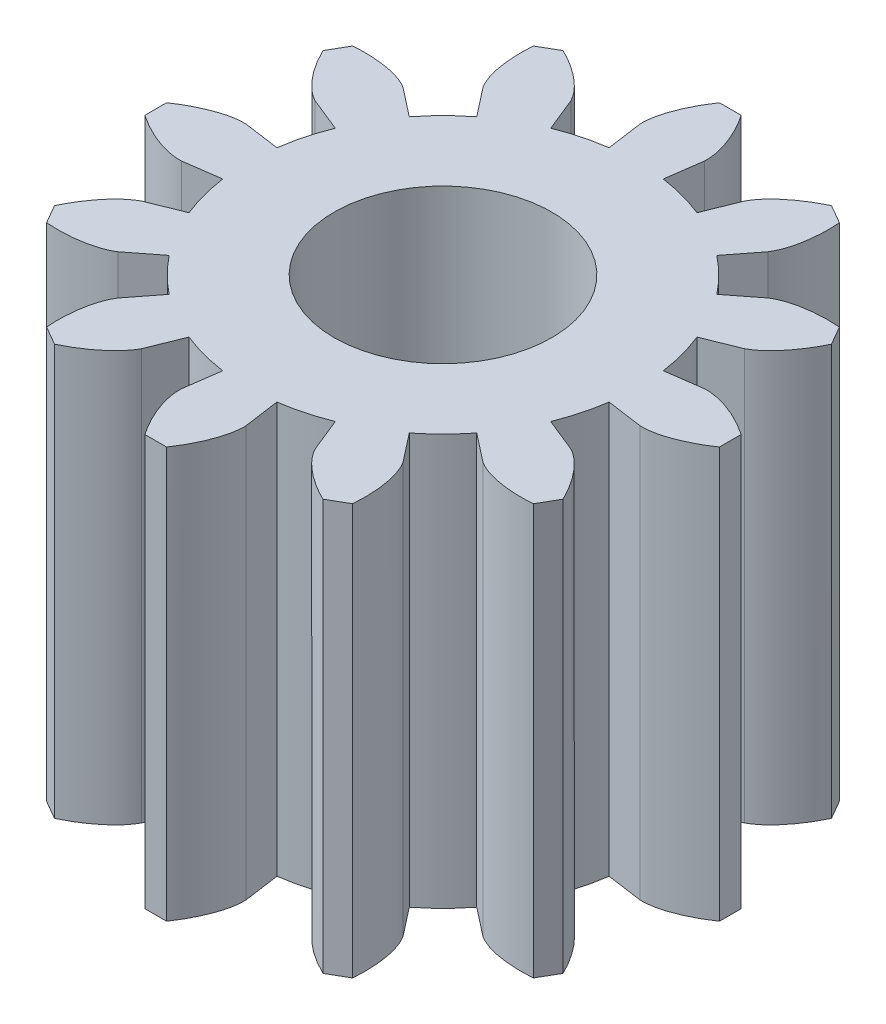
SolidWorks part; units mm, degrees
ref_plane "Front Plane" through (0, 0, 0) normal (0, 0, 1) x (1, 0, 0)
ref_plane "Top Plane" through (0, 0, 0) normal (0, 1, 0) x (1, 0, 0)
ref_plane "Right Plane" through (0, 0, 0) normal (1, 0, 0) x (0, 0, -1)
ref_plane "Plane1" through (0, -5, 0) normal (0, -1, 0) x (1, 0, 0)
sketch "Sketch1" plane through (0, -5, 0) normal (0, -1, 0) x (1, 0, 0)
  line L0 (3.7441, -2.923) -> (4.4442, -3.4696)
  line L1 (5.9256, -3.7266) -> (6.1901, -3.2684)
  line L2 (5.2268, -2.114) -> (4.4035, -1.781)
  line L3 (4.704, -0.6593) -> (5.5836, -0.7826)
  line L4 (6.995, -0.2646) -> (6.995, 0.2646)
  line L5 (5.5836, 0.7826) -> (4.704, 0.6593)
  line L6 (4.4035, 1.781) -> (5.2268, 2.114)
  line L7 (6.1901, 3.2684) -> (5.9256, 3.7266)
  line L8 (4.4442, 3.4696) -> (3.7441, 2.923)
  line L9 (2.923, 3.7441) -> (3.4696, 4.4442)
  line L10 (3.7266, 5.9256) -> (3.2684, 6.1901)
  line L11 (2.114, 5.2268) -> (1.781, 4.4035)
  line L12 (0.6593, 4.704) -> (0.7826, 5.5836)
  line L13 (0.2646, 6.995) -> (-0.2646, 6.995)
  line L14 (-0.7826, 5.5836) -> (-0.6593, 4.704)
  line L15 (-1.781, 4.4035) -> (-2.114, 5.2268)
  line L16 (-3.2684, 6.1901) -> (-3.7266, 5.9256)
  line L17 (-3.4696, 4.4442) -> (-2.923, 3.7441)
  line L18 (-3.7441, 2.923) -> (-4.4442, 3.4696)
  line L19 (-5.9256, 3.7266) -> (-6.1901, 3.2684)
  line L20 (-5.2268, 2.114) -> (-4.4035, 1.781)
  line L21 (-4.704, 0.6593) -> (-5.5836, 0.7826)
  line L22 (-6.995, 0.2646) -> (-6.995, -0.2646)
  line L23 (-5.5836, -0.7826) -> (-4.704, -0.6593)
  line L24 (-4.4035, -1.781) -> (-5.2268, -2.114)
  line L25 (-6.1901, -3.2684) -> (-5.9256, -3.7266)
  line L26 (-4.4442, -3.4696) -> (-3.7441, -2.923)
  line L27 (-2.923, -3.7441) -> (-3.4696, -4.4442)
  line L28 (-3.7266, -5.9256) -> (-3.2684, -6.1901)
  line L29 (-2.114, -5.2268) -> (-1.781, -4.4035)
  line L30 (-0.6593, -4.704) -> (-0.7826, -5.5836)
  line L31 (-0.2646, -6.995) -> (0.2646, -6.995)
  line L32 (0.7826, -5.5836) -> (0.6593, -4.704)
  line L33 (1.781, -4.4035) -> (2.114, -5.2268)
  line L34 (3.2684, -6.1901) -> (3.7266, -5.9256)
  line L35 (3.4696, -4.4442) -> (2.923, -3.7441)
  arc A0 (2.923, -3.7441) -> (3.7441, -2.923) centre (0, 0) ccw
  arc A1 (4.4035, -1.781) -> (4.704, -0.6593) centre (0, 0) ccw
  arc A2 (4.704, 0.6593) -> (4.4035, 1.781) centre (0, 0) ccw
  arc A3 (3.7441, 2.923) -> (2.923, 3.7441) centre (0, 0) ccw
  arc A4 (1.781, 4.4035) -> (0.6593, 4.704) centre (0, 0) ccw
  arc A5 (-0.6593, 4.704) -> (-1.781, 4.4035) centre (0, 0) ccw
  arc A6 (-2.923, 3.7441) -> (-3.7441, 2.923) centre (0, 0) ccw
  arc A7 (-4.4035, 1.781) -> (-4.704, 0.6593) centre (0, 0) ccw
  arc A8 (-4.704, -0.6593) -> (-4.4035, -1.781) centre (0, 0) ccw
  arc A9 (-3.7441, -2.923) -> (-2.923, -3.7441) centre (0, 0) ccw
  arc A10 (-1.781, -4.4035) -> (-0.6593, -4.704) centre (0, 0) ccw
  arc A11 (0.6593, -4.704) -> (1.781, -4.4035) centre (0, 0) ccw
  ellipse E0 centre (5.8654, -2.9875) end of major axis (7.546, -2.8631) minor radius 0.7415 (4.4442, -3.4696) -> (5.9256, -3.7266) ccw
  ellipse E1 centre (5.5279, -3.5513) end of major axis (6.2585, -5.0325) minor radius 0.7192 (6.1901, -3.2684) -> (5.2268, -2.114) ccw
  ellipse E2 centre (6.5733, 0.3454) end of major axis (7.9666, 1.2935) minor radius 0.7415 (5.5836, -0.7826) -> (6.995, -0.2646) ccw
  ellipse E3 centre (6.563, -0.3115) end of major axis (7.9362, -1.229) minor radius 0.7192 (6.995, 0.2646) -> (5.5836, 0.7826) ccw
  ellipse E4 centre (5.5199, 3.5858) end of major axis (4.7874, 2.068) minor radius 0.7415 (5.2268, 2.114) -> (6.1901, 3.2684) ccw
  ellipse E5 centre (5.8394, 3.0117) end of major axis (7.4875, 2.9038) minor radius 0.7192 (5.9256, 3.7266) -> (4.4442, 3.4696) ccw
  ellipse E6 centre (2.9875, 5.8654) end of major axis (3.112, 4.1847) minor radius 0.7415 (3.4696, 4.4442) -> (3.7266, 5.9256) ccw
  ellipse E7 centre (3.5513, 5.5279) end of major axis (5.0325, 6.2585) minor radius 0.7192 (3.2684, 6.1901) -> (2.114, 5.2268) ccw
  ellipse E8 centre (-0.3454, 6.5733) end of major axis (0.6027, 5.18) minor radius 0.7415 (0.7826, 5.5836) -> (0.2646, 6.995) ccw
  ellipse E9 centre (0.3115, 6.563) end of major axis (-0.606, 5.1897) minor radius 0.7192 (-0.2646, 6.995) -> (-0.7826, 5.5836) ccw
  ellipse E10 centre (-3.5858, 5.5199) end of major axis (-2.068, 4.7874) minor radius 0.7415 (-2.114, 5.2268) -> (-3.2684, 6.1901) ccw
  ellipse E11 centre (-3.0117, 5.8394) end of major axis (-3.1197, 4.1914) minor radius 0.7192 (-3.7266, 5.9256) -> (-3.4696, 4.4442) ccw
  ellipse E12 centre (-5.8654, 2.9875) end of major axis (-4.1847, 3.112) minor radius 0.7415 (-4.4442, 3.4696) -> (-5.9256, 3.7266) ccw
  ellipse E13 centre (-5.5279, 3.5513) end of major axis (-4.7974, 2.07) minor radius 0.7192 (-6.1901, 3.2684) -> (-5.2268, 2.114) ccw
  ellipse E14 centre (-6.5733, -0.3454) end of major axis (-5.18, 0.6027) minor radius 0.7415 (-5.5836, 0.7826) -> (-6.995, 0.2646) ccw
  ellipse E15 centre (-6.563, 0.3115) end of major axis (-5.1897, -0.606) minor radius 0.7192 (-6.995, -0.2646) -> (-5.5836, -0.7826) ccw
  ellipse E16 centre (-5.5199, -3.5858) end of major axis (-6.2525, -5.1035) minor radius 0.7415 (-5.2268, -2.114) -> (-6.1901, -3.2684) ccw
  ellipse E17 centre (-5.8394, -3.0117) end of major axis (-4.1914, -3.1197) minor radius 0.7192 (-5.9256, -3.7266) -> (-4.4442, -3.4696) ccw
  ellipse E18 centre (-2.9875, -5.8654) end of major axis (-2.8631, -7.546) minor radius 0.7415 (-3.4696, -4.4442) -> (-3.7266, -5.9256) ccw
  ellipse E19 centre (-3.5513, -5.5279) end of major axis (-5.0325, -6.2585) minor radius 0.7192 (-3.2684, -6.1901) -> (-2.114, -5.2268) ccw
  ellipse E20 centre (0.3454, -6.5733) end of major axis (1.2935, -7.9666) minor radius 0.7415 (-0.7826, -5.5836) -> (-0.2646, -6.995) ccw
  ellipse E21 centre (-0.3115, -6.563) end of major axis (-1.229, -7.9362) minor radius 0.7192 (0.2646, -6.995) -> (0.7826, -5.5836) ccw
  ellipse E22 centre (3.5858, -5.5199) end of major axis (5.1035, -6.2525) minor radius 0.7415 (2.114, -5.2268) -> (3.2684, -6.1901) ccw
  ellipse E23 centre (3.0117, -5.8394) end of major axis (2.9038, -7.4875) minor radius 0.7192 (3.7266, -5.9256) -> (3.4696, -4.4442) ccw
  point P4 (5.8654, -2.9875)
  point P5 (7.546, -2.8631)
  point P6 (5.9201, -3.727)
  point P7 (4.4442, -3.4696)
  point P8 (5.9256, -3.7266)
  point P9 (5.1439, -3.7018)
  point P10 (6.5868, -2.2732)
  point P18 (5.5279, -3.5513)
  point P19 (6.173, -3.2331)
  point P20 (6.2585, -5.0325)
  point P21 (6.1901, -3.2684)
  point P22 (5.2268, -2.114)
  point P23 (5.7778, -2.6038)
  point P24 (5.2781, -4.4987)
  point P34 (6.5733, 0.3454)
  point P35 (7.9666, 1.2935)
  point P36 (6.9905, -0.2677)
  point P37 (5.5836, -0.7826)
  point P38 (6.995, -0.2646)
  point P39 (6.3057, -0.6339)
  point P40 (6.8409, 1.3247)
  point P48 (6.563, -0.3115)
  point P49 (7.9362, -1.229)
  point P50 (6.1634, -0.9095)
  point P51 (6.995, 0.2646)
  point P52 (5.5836, 0.7826)
  point P53 (6.3057, 0.6339)
  point P54 (6.8203, -1.2569)
  point P64 (5.5199, 3.5858)
  point P65 (6.1878, 3.2634)
  point P66 (4.7874, 2.068)
  point P67 (5.2268, 2.114)
  point P68 (6.1901, 3.2684)
  point P69 (5.7778, 2.6038)
  point P70 (5.2621, 4.5677)
  point P78 (5.8394, 3.0117)
  point P79 (7.4875, 2.9038)
  point P80 (5.7924, 2.294)
  point P81 (5.9256, 3.7266)
  point P82 (4.4442, 3.4696)
  point P83 (5.1439, 3.7018)
  point P84 (6.535, 2.3216)
  point P94 (2.9875, 5.8654)
  point P95 (3.727, 5.9201)
  point P96 (3.112, 4.1847)
  point P97 (3.4696, 4.4442)
  point P98 (3.7266, 5.9256)
  point P99 (3.7018, 5.1439)
  point P100 (2.2732, 6.5868)
  point P108 (3.5513, 5.5279)
  point P109 (5.0325, 6.2585)
  point P110 (3.8694, 4.8829)
  point P111 (3.2684, 6.1901)
  point P112 (2.114, 5.2268)
  point P113 (2.6038, 5.7778)
  point P114 (4.4987, 5.2781)
  point P124 (-0.3454, 6.5733)
  point P125 (0.2677, 6.9905)
  point P126 (0.6027, 5.18)
  point P127 (0.7826, 5.5836)
  point P128 (0.2646, 6.995)
  point P129 (0.6339, 6.3057)
  point P130 (-1.3247, 6.8409)
  point P138 (0.3115, 6.563)
  point P139 (0.9095, 6.1634)
  point P140 (-0.606, 5.1897)
  point P141 (-0.2646, 6.995)
  point P142 (-0.7826, 5.5836)
  point P143 (-0.6339, 6.3057)
  point P144 (1.2569, 6.8203)
  point P154 (-3.5858, 5.5199)
  point P155 (-2.068, 4.7874)
  point P156 (-3.9081, 4.8521)
  point P157 (-2.114, 5.2268)
  point P158 (-3.2684, 6.1901)
  point P159 (-2.6038, 5.7778)
  point P160 (-4.5677, 5.2621)
  point P168 (-3.0117, 5.8394)
  point P169 (-2.294, 5.7924)
  point P170 (-3.1197, 4.1914)
  point P171 (-3.7266, 5.9256)
  point P172 (-3.4696, 4.4442)
  point P173 (-3.7018, 5.1439)
  point P174 (-2.3216, 6.535)
  point P184 (-5.8654, 2.9875)
  point P185 (-4.1847, 3.112)
  point P186 (-5.8106, 2.248)
  point P187 (-4.4442, 3.4696)
  point P188 (-5.9256, 3.7266)
  point P189 (-5.1439, 3.7018)
  point P190 (-6.5868, 2.2732)
  point P198 (-5.5279, 3.5513)
  point P199 (-4.8829, 3.8694)
  point P200 (-4.7974, 2.07)
  point P201 (-6.1901, 3.2684)
  point P202 (-5.2268, 2.114)
  point P203 (-5.7778, 2.6038)
  point P204 (-5.2781, 4.4987)
  point P214 (-6.5733, -0.3454)
  point P215 (-5.18, 0.6027)
  point P216 (-6.1561, -0.9585)
  point P217 (-5.5836, 0.7826)
  point P218 (-6.995, 0.2646)
  point P219 (-6.3057, 0.6339)
  point P220 (-6.8409, -1.3247)
  point P228 (-6.563, 0.3115)
  point P229 (-5.1897, -0.606)
  point P230 (-6.9625, -0.2865)
  point P231 (-6.995, -0.2646)
  point P232 (-5.5836, -0.7826)
  point P233 (-6.3057, -0.6339)
  point P234 (-6.8203, 1.2569)
  point P244 (-5.5199, -3.5858)
  point P245 (-4.8521, -3.9081)
  point P246 (-6.2525, -5.1035)
  point P247 (-5.2268, -2.114)
  point P248 (-6.1901, -3.2684)
  point P249 (-5.7778, -2.6038)
  point P250 (-5.2621, -4.5677)
  point P258 (-5.8394, -3.0117)
  point P259 (-4.1914, -3.1197)
  point P260 (-5.8865, -3.7294)
  point P261 (-5.9256, -3.7266)
  point P262 (-4.4442, -3.4696)
  point P263 (-5.1439, -3.7018)
  point P264 (-6.535, -2.3216)
  point P274 (-2.9875, -5.8654)
  point P275 (-2.248, -5.8106)
  point P276 (-2.8631, -7.546)
  point P277 (-3.4696, -4.4442)
  point P278 (-3.7266, -5.9256)
  point P279 (-3.7018, -5.1439)
  point P280 (-2.2732, -6.5868)
  point P288 (-3.5513, -5.5279)
  point P289 (-2.07, -4.7974)
  point P290 (-3.2331, -6.173)
  point P291 (-3.2684, -6.1901)
  point P292 (-2.114, -5.2268)
  point P293 (-2.6038, -5.7778)
  point P294 (-4.4987, -5.2781)
  point P304 (0.3454, -6.5733)
  point P305 (0.9585, -6.1561)
  point P306 (1.2935, -7.9666)
  point P307 (-0.7826, -5.5836)
  point P308 (-0.2646, -6.995)
  point P309 (-0.6339, -6.3057)
  point P310 (1.3247, -6.8409)
  point P318 (-0.3115, -6.563)
  point P319 (0.2865, -6.9625)
  point P320 (-1.229, -7.9362)
  point P321 (0.2646, -6.995)
  point P322 (0.7826, -5.5836)
  point P323 (0.6339, -6.3057)
  point P324 (-1.2569, -6.8203)
  point P334 (3.5858, -5.5199)
  point P335 (5.1035, -6.2525)
  point P336 (3.2634, -6.1878)
  point P337 (2.114, -5.2268)
  point P338 (3.2684, -6.1901)
  point P339 (2.6038, -5.7778)
  point P340 (4.5677, -5.2621)
  point P348 (3.0117, -5.8394)
  point P349 (3.7294, -5.8865)
  point P350 (2.9038, -7.4875)
  point P351 (3.7266, -5.9256)
  point P352 (3.4696, -4.4442)
  point P353 (3.7018, -5.1439)
  point P354 (2.3216, -6.535)
extrude "Boss-Extrude1" add sketch "Sketch1" against normal blind 5
sketch "Sketch3" plane through (0, 0, 0) normal (0, 1, 0) x (1, 0, 0)
  line L36 (2.923, 3.7441) -> (3.4696, 4.4442)
  line L37 (3.7266, 5.9256) -> (3.2684, 6.1901)
  line L38 (2.114, 5.2268) -> (1.781, 4.4035)
  line L39 (0.6593, 4.704) -> (0.7826, 5.5836)
  line L40 (0.2646, 6.995) -> (-0.2646, 6.995)
  line L41 (-0.7826, 5.5836) -> (-0.6593, 4.704)
  line L42 (-1.781, 4.4035) -> (-2.114, 5.2268)
  line L43 (-3.2684, 6.1901) -> (-3.7266, 5.9256)
  line L44 (-3.4696, 4.4442) -> (-2.923, 3.7441)
  line L45 (-3.7441, 2.923) -> (-4.4442, 3.4696)
  line L46 (-5.9256, 3.7266) -> (-6.1901, 3.2684)
  line L47 (-5.2268, 2.114) -> (-4.4035, 1.781)
  line L48 (-4.704, 0.6593) -> (-5.5836, 0.7826)
  line L49 (-6.995, 0.2646) -> (-6.995, -0.2646)
  line L50 (-5.5836, -0.7826) -> (-4.704, -0.6593)
  line L51 (-4.4035, -1.781) -> (-5.2268, -2.114)
  line L52 (-6.1901, -3.2684) -> (-5.9256, -3.7266)
  line L53 (-4.4442, -3.4696) -> (-3.7441, -2.923)
  line L54 (-2.923, -3.7441) -> (-3.4696, -4.4442)
  line L55 (-3.7266, -5.9256) -> (-3.2684, -6.1901)
  line L56 (-2.114, -5.2268) -> (-1.781, -4.4035)
  line L57 (-0.6593, -4.704) -> (-0.7826, -5.5836)
  line L58 (-0.2646, -6.995) -> (0.2646, -6.995)
  line L59 (0.7826, -5.5836) -> (0.6593, -4.704)
  line L60 (1.781, -4.4035) -> (2.114, -5.2268)
  line L61 (3.2684, -6.1901) -> (3.7266, -5.9256)
  line L62 (3.4696, -4.4442) -> (2.923, -3.7441)
  line L63 (3.7441, -2.923) -> (4.4442, -3.4696)
  line L64 (5.9256, -3.7266) -> (6.1901, -3.2684)
  line L65 (5.2268, -2.114) -> (4.4035, -1.781)
  line L66 (4.704, -0.6593) -> (5.5836, -0.7826)
  line L67 (6.995, -0.2646) -> (6.995, 0.2646)
  line L68 (5.5836, 0.7826) -> (4.704, 0.6593)
  line L69 (4.4035, 1.781) -> (5.2268, 2.114)
  line L70 (6.1901, 3.2684) -> (5.9256, 3.7266)
  line L71 (4.4442, 3.4696) -> (3.7441, 2.923)
  line L72 (2.923, 3.7441) -> (3.4696, 4.4442)
  line L73 (3.7266, 5.9256) -> (3.2684, 6.1901)
  line L74 (2.114, 5.2268) -> (1.781, 4.4035)
  line L75 (0.6593, 4.704) -> (0.7826, 5.5836)
  line L76 (0.2646, 6.995) -> (-0.2646, 6.995)
  line L77 (-0.7826, 5.5836) -> (-0.6593, 4.704)
  line L78 (-1.781, 4.4035) -> (-2.114, 5.2268)
  line L79 (-3.2684, 6.1901) -> (-3.7266, 5.9256)
  line L80 (-3.4696, 4.4442) -> (-2.923, 3.7441)
  line L81 (-3.7441, 2.923) -> (-4.4442, 3.4696)
  line L82 (-5.9256, 3.7266) -> (-6.1901, 3.2684)
  line L83 (-5.2268, 2.114) -> (-4.4035, 1.781)
  line L84 (-4.704, 0.6593) -> (-5.5836, 0.7826)
  line L85 (-6.995, 0.2646) -> (-6.995, -0.2646)
  line L86 (-5.5836, -0.7826) -> (-4.704, -0.6593)
  line L87 (-4.4035, -1.781) -> (-5.2268, -2.114)
  line L88 (-6.1901, -3.2684) -> (-5.9256, -3.7266)
  line L89 (-4.4442, -3.4696) -> (-3.7441, -2.923)
  line L90 (-2.923, -3.7441) -> (-3.4696, -4.4442)
  line L91 (-3.7266, -5.9256) -> (-3.2684, -6.1901)
  line L92 (-2.114, -5.2268) -> (-1.781, -4.4035)
  line L93 (-0.6593, -4.704) -> (-0.7826, -5.5836)
  line L94 (-0.2646, -6.995) -> (0.2646, -6.995)
  line L95 (0.7826, -5.5836) -> (0.6593, -4.704)
  line L96 (1.781, -4.4035) -> (2.114, -5.2268)
  line L97 (3.2684, -6.1901) -> (3.7266, -5.9256)
  line L98 (3.4696, -4.4442) -> (2.923, -3.7441)
  line L99 (3.7441, -2.923) -> (4.4442, -3.4696)
  line L100 (5.9256, -3.7266) -> (6.1901, -3.2684)
  line L101 (5.2268, -2.114) -> (4.4035, -1.781)
  line L102 (4.704, -0.6593) -> (5.5836, -0.7826)
  line L103 (6.995, -0.2646) -> (6.995, 0.2646)
  line L104 (5.5836, 0.7826) -> (4.704, 0.6593)
  line L105 (4.4035, 1.781) -> (5.2268, 2.114)
  line L106 (6.1901, 3.2684) -> (5.9256, 3.7266)
  line L107 (4.4442, 3.4696) -> (3.7441, 2.923)
  arc A12 (3.7441, 2.923) -> (2.923, 3.7441) centre (0, 0) ccw
  arc A13 (1.781, 4.4035) -> (0.6593, 4.704) centre (0, 0) ccw
  arc A14 (-0.6593, 4.704) -> (-1.781, 4.4035) centre (0, 0) ccw
  arc A15 (-2.923, 3.7441) -> (-3.7441, 2.923) centre (0, 0) ccw
  arc A16 (-4.4035, 1.781) -> (-4.704, 0.6593) centre (0, 0) ccw
  arc A17 (-4.704, -0.6593) -> (-4.4035, -1.781) centre (0, 0) ccw
  arc A18 (-3.7441, -2.923) -> (-2.923, -3.7441) centre (0, 0) ccw
  arc A19 (-1.781, -4.4035) -> (-0.6593, -4.704) centre (0, 0) ccw
  arc A20 (0.6593, -4.704) -> (1.781, -4.4035) centre (0, 0) ccw
  arc A21 (2.923, -3.7441) -> (3.7441, -2.923) centre (0, 0) ccw
  arc A22 (4.4035, -1.781) -> (4.704, -0.6593) centre (0, 0) ccw
  arc A23 (4.704, 0.6593) -> (4.4035, 1.781) centre (0, 0) ccw
  arc A24 (3.7441, 2.923) -> (2.923, 3.7441) centre (0, 0) ccw
  arc A25 (1.781, 4.4035) -> (0.6593, 4.704) centre (0, 0) ccw
  arc A26 (-0.6593, 4.704) -> (-1.781, 4.4035) centre (0, 0) ccw
  arc A27 (-2.923, 3.7441) -> (-3.7441, 2.923) centre (0, 0) ccw
  arc A28 (-4.4035, 1.781) -> (-4.704, 0.6593) centre (0, 0) ccw
  arc A29 (-4.704, -0.6593) -> (-4.4035, -1.781) centre (0, 0) ccw
  arc A30 (-3.7441, -2.923) -> (-2.923, -3.7441) centre (0, 0) ccw
  arc A31 (-1.781, -4.4035) -> (-0.6593, -4.704) centre (0, 0) ccw
  arc A32 (0.6593, -4.704) -> (1.781, -4.4035) centre (0, 0) ccw
  arc A33 (2.923, -3.7441) -> (3.7441, -2.923) centre (0, 0) ccw
  arc A34 (4.4035, -1.781) -> (4.704, -0.6593) centre (0, 0) ccw
  arc A35 (4.704, 0.6593) -> (4.4035, 1.781) centre (0, 0) ccw
  ellipse E24 centre (3.0117, 5.8394) end of major axis (2.9038, 7.4875) minor radius 0.7192 (3.4696, 4.4442) -> (3.7266, 5.9256) ccw
  ellipse E25 centre (3.5858, 5.5199) end of major axis (2.068, 4.7874) minor radius 0.7415 (3.2684, 6.1901) -> (2.114, 5.2268) ccw
  ellipse E26 centre (-0.3115, 6.563) end of major axis (-1.229, 7.9362) minor radius 0.7192 (0.7826, 5.5836) -> (0.2646, 6.995) ccw
  ellipse E27 centre (0.3454, 6.5733) end of major axis (1.2935, 7.9666) minor radius 0.7415 (-0.2646, 6.995) -> (-0.7826, 5.5836) ccw
  ellipse E28 centre (-3.5513, 5.5279) end of major axis (-2.07, 4.7974) minor radius 0.7192 (-2.114, 5.2268) -> (-3.2684, 6.1901) ccw
  ellipse E29 centre (-2.9875, 5.8654) end of major axis (-2.8631, 7.546) minor radius 0.7415 (-3.7266, 5.9256) -> (-3.4696, 4.4442) ccw
  ellipse E30 centre (-5.8394, 3.0117) end of major axis (-4.1914, 3.1197) minor radius 0.7192 (-4.4442, 3.4696) -> (-5.9256, 3.7266) ccw
  ellipse E31 centre (-5.5199, 3.5858) end of major axis (-6.2525, 5.1035) minor radius 0.7415 (-6.1901, 3.2684) -> (-5.2268, 2.114) ccw
  ellipse E32 centre (-6.563, -0.3115) end of major axis (-5.1897, 0.606) minor radius 0.7192 (-5.5836, 0.7826) -> (-6.995, 0.2646) ccw
  ellipse E33 centre (-6.5733, 0.3454) end of major axis (-7.9666, 1.2935) minor radius 0.7415 (-6.995, -0.2646) -> (-5.5836, -0.7826) ccw
  ellipse E34 centre (-5.5279, -3.5513) end of major axis (-6.2585, -5.0325) minor radius 0.7192 (-5.2268, -2.114) -> (-6.1901, -3.2684) ccw
  ellipse E35 centre (-5.8654, -2.9875) end of major axis (-4.1847, -3.112) minor radius 0.7415 (-5.9256, -3.7266) -> (-4.4442, -3.4696) ccw
  ellipse E36 centre (-3.0117, -5.8394) end of major axis (-3.1197, -4.1914) minor radius 0.7192 (-3.4696, -4.4442) -> (-3.7266, -5.9256) ccw
  ellipse E37 centre (-3.5858, -5.5199) end of major axis (-5.1035, -6.2525) minor radius 0.7415 (-3.2684, -6.1901) -> (-2.114, -5.2268) ccw
  ellipse E38 centre (0.3115, -6.563) end of major axis (-0.606, -5.1897) minor radius 0.7192 (-0.7826, -5.5836) -> (-0.2646, -6.995) ccw
  ellipse E39 centre (-0.3454, -6.5733) end of major axis (0.6027, -5.18) minor radius 0.7415 (0.2646, -6.995) -> (0.7826, -5.5836) ccw
  ellipse E40 centre (3.5513, -5.5279) end of major axis (5.0325, -6.2585) minor radius 0.7192 (2.114, -5.2268) -> (3.2684, -6.1901) ccw
  ellipse E41 centre (2.9875, -5.8654) end of major axis (3.112, -4.1847) minor radius 0.7415 (3.7266, -5.9256) -> (3.4696, -4.4442) ccw
  ellipse E42 centre (5.8394, -3.0117) end of major axis (7.4875, -2.9038) minor radius 0.7192 (4.4442, -3.4696) -> (5.9256, -3.7266) ccw
  ellipse E43 centre (5.5199, -3.5858) end of major axis (4.7874, -2.068) minor radius 0.7415 (6.1901, -3.2684) -> (5.2268, -2.114) ccw
  ellipse E44 centre (6.563, 0.3115) end of major axis (7.9362, 1.229) minor radius 0.7192 (5.5836, -0.7826) -> (6.995, -0.2646) ccw
  ellipse E45 centre (6.5733, -0.3454) end of major axis (7.9666, -1.2935) minor radius 0.7415 (6.995, 0.2646) -> (5.5836, 0.7826) ccw
  ellipse E46 centre (5.5279, 3.5513) end of major axis (6.2585, 5.0325) minor radius 0.7192 (5.2268, 2.114) -> (6.1901, 3.2684) ccw
  ellipse E47 centre (5.8654, 2.9875) end of major axis (7.546, 2.8631) minor radius 0.7415 (5.9256, 3.7266) -> (4.4442, 3.4696) ccw
  ellipse E48 centre (3.0117, 5.8394) end of major axis (2.9038, 7.4875) minor radius 0.7192 (3.4696, 4.4442) -> (3.7266, 5.9256) ccw
  ellipse E49 centre (3.5858, 5.5199) end of major axis (5.1035, 6.2525) minor radius 0.7415 (3.2684, 6.1901) -> (2.114, 5.2268) ccw
  ellipse E50 centre (-0.3115, 6.563) end of major axis (-1.229, 7.9362) minor radius 0.7192 (0.7826, 5.5836) -> (0.2646, 6.995) ccw
  ellipse E51 centre (0.3454, 6.5733) end of major axis (1.2935, 7.9666) minor radius 0.7415 (-0.2646, 6.995) -> (-0.7826, 5.5836) ccw
  ellipse E52 centre (-3.5513, 5.5279) end of major axis (-2.07, 4.7974) minor radius 0.7192 (-2.114, 5.2268) -> (-3.2684, 6.1901) ccw
  ellipse E53 centre (-2.9875, 5.8654) end of major axis (-2.8631, 7.546) minor radius 0.7415 (-3.7266, 5.9256) -> (-3.4696, 4.4442) ccw
  ellipse E54 centre (-5.8394, 3.0117) end of major axis (-4.1914, 3.1197) minor radius 0.7192 (-4.4442, 3.4696) -> (-5.9256, 3.7266) ccw
  ellipse E55 centre (-5.5199, 3.5858) end of major axis (-6.2525, 5.1035) minor radius 0.7415 (-6.1901, 3.2684) -> (-5.2268, 2.114) ccw
  ellipse E56 centre (-6.563, -0.3115) end of major axis (-5.1897, 0.606) minor radius 0.7192 (-5.5836, 0.7826) -> (-6.995, 0.2646) ccw
  ellipse E57 centre (-6.5733, 0.3454) end of major axis (-7.9666, 1.2935) minor radius 0.7415 (-6.995, -0.2646) -> (-5.5836, -0.7826) ccw
  ellipse E58 centre (-5.5279, -3.5513) end of major axis (-6.2585, -5.0325) minor radius 0.7192 (-5.2268, -2.114) -> (-6.1901, -3.2684) ccw
  ellipse E59 centre (-5.8654, -2.9875) end of major axis (-4.1847, -3.112) minor radius 0.7415 (-5.9256, -3.7266) -> (-4.4442, -3.4696) ccw
  ellipse E60 centre (-3.0117, -5.8394) end of major axis (-3.1197, -4.1914) minor radius 0.7192 (-3.4696, -4.4442) -> (-3.7266, -5.9256) ccw
  ellipse E61 centre (-3.5858, -5.5199) end of major axis (-5.1035, -6.2525) minor radius 0.7415 (-3.2684, -6.1901) -> (-2.114, -5.2268) ccw
  ellipse E62 centre (0.3115, -6.563) end of major axis (-0.606, -5.1897) minor radius 0.7192 (-0.7826, -5.5836) -> (-0.2646, -6.995) ccw
  ellipse E63 centre (-0.3454, -6.5733) end of major axis (0.6027, -5.18) minor radius 0.7415 (0.2646, -6.995) -> (0.7826, -5.5836) ccw
  ellipse E64 centre (3.5513, -5.5279) end of major axis (5.0325, -6.2585) minor radius 0.7192 (2.114, -5.2268) -> (3.2684, -6.1901) ccw
  ellipse E65 centre (2.9875, -5.8654) end of major axis (3.112, -4.1847) minor radius 0.7415 (3.7266, -5.9256) -> (3.4696, -4.4442) ccw
  ellipse E66 centre (5.8394, -3.0117) end of major axis (7.4875, -2.9038) minor radius 0.7192 (4.4442, -3.4696) -> (5.9256, -3.7266) ccw
  ellipse E67 centre (5.5199, -3.5858) end of major axis (4.7874, -2.068) minor radius 0.7415 (6.1901, -3.2684) -> (5.2268, -2.114) ccw
  ellipse E68 centre (6.563, 0.3115) end of major axis (7.9362, 1.229) minor radius 0.7192 (5.5836, -0.7826) -> (6.995, -0.2646) ccw
  ellipse E69 centre (6.5733, -0.3454) end of major axis (7.9666, -1.2935) minor radius 0.7415 (6.995, 0.2646) -> (5.5836, 0.7826) ccw
  ellipse E70 centre (5.5279, 3.5513) end of major axis (6.2585, 5.0325) minor radius 0.7192 (5.2268, 2.114) -> (6.1901, 3.2684) ccw
  ellipse E71 centre (5.8654, 2.9875) end of major axis (7.546, 2.8631) minor radius 0.7415 (5.9256, 3.7266) -> (4.4442, 3.4696) ccw
  dimension "D1" = 0
extrude "Boss-Extrude2" add sketch "Sketch3" along normal blind 5
sketch "Sketch2" plane through (0, -5, 0) normal (0, 1, 0) x (1, 0, 0)
  circle A0 centre (0, 0) radius 2.65
  dimension "D1" = 5.3
extrude "Cut-Extrude1" cut sketch "Sketch2" against normal through all both and the other way through all
